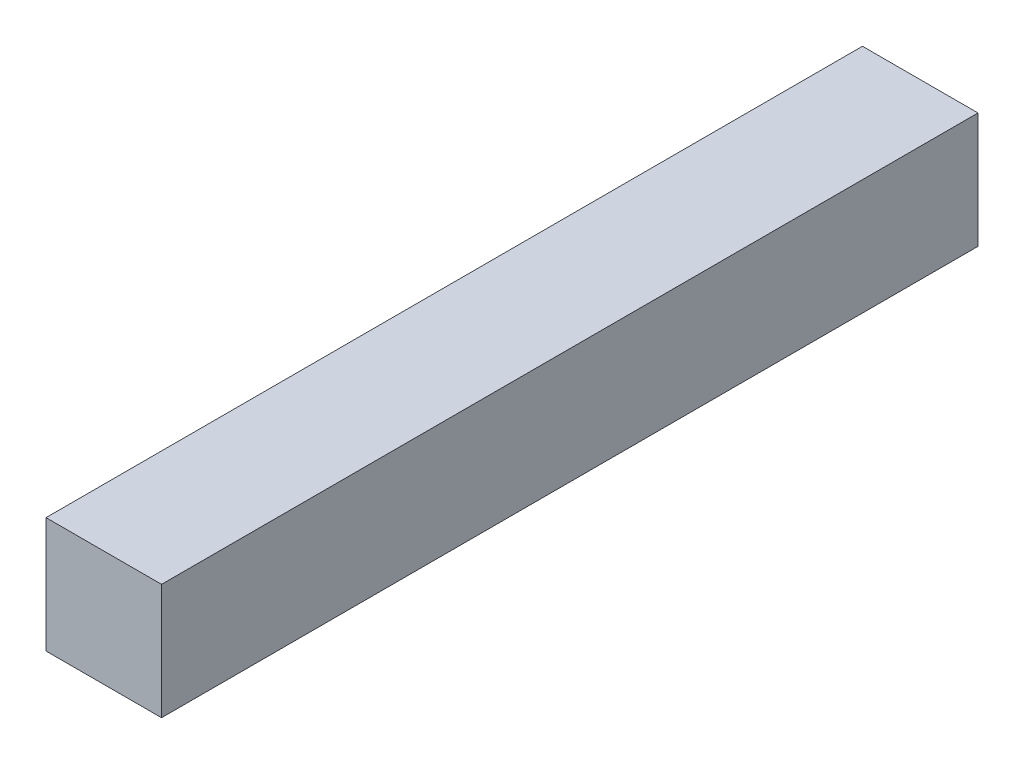
SolidWorks part; units mm, degrees
ref_plane "Front" through (0, 0, 0) normal (0, 0, 1) x (1, 0, 0)
ref_plane "Top" through (0, 0, 0) normal (0, 1, 0) x (1, 0, 0)
ref_plane "Right" through (0, 0, 0) normal (1, 0, 0) x (0, 0, -1)
sketch "sketch1" plane through (0, 0, 0) normal (0, 0, 1) x (1, 0, 0)
  line L0 (2.3812, 2.3813) -> (-2.3813, -2.3812) construction
  line L1 (-2.3813, 2.3813) -> (2.3812, 2.3813)
  line L2 (-2.3813, 2.3813) -> (-2.3813, -2.3812)
  line L3 (-2.3813, -2.3812) -> (2.3812, -2.3812)
  line L4 (2.3812, 2.3813) -> (2.3812, -2.3812)
  dimension "W" = 4.7625
  dimension "H" = 4.7625
extrude "Extrude1" add sketch "sketch1" along normal blind 33.655
